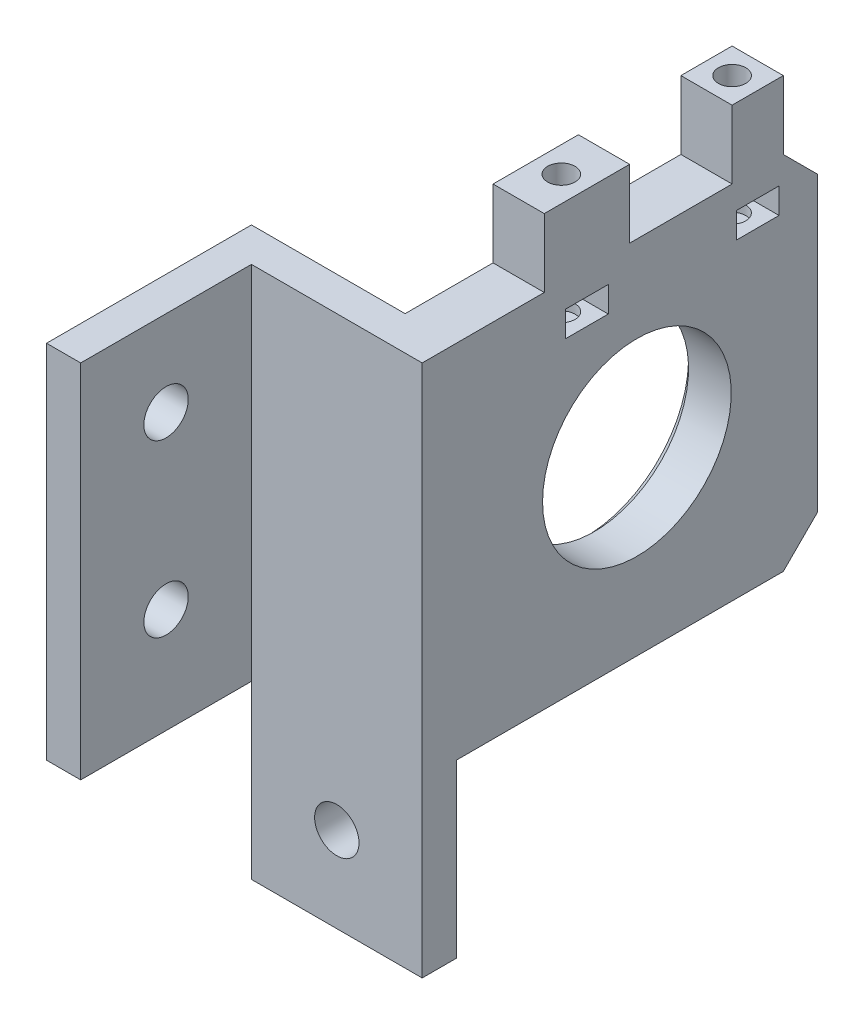
SolidWorks part; units mm, degrees
ref_plane "Přední rovina" through (0, 0, 0) normal (0, 0, 1) x (1, 0, 0)
ref_plane "Horní rovina" through (0, 0, 0) normal (0, 1, 0) x (1, 0, 0)
ref_plane "Pravá rovina" through (0, 0, 0) normal (1, 0, 0) x (0, 0, -1)
sketch "Skica2" plane through (0, 0, 0) normal (0, 0, 1) x (1, 0, 0)
  line L0 (-24.5243, -350) -> (-24.5243, 0) construction
  line L1 (-4.5243, -40) -> (-24.5243, -40)
  line L2 (-4.5243, -40) -> (-4.5243, -82.3)
  line L3 (-4.5243, -82.3) -> (-24.5243, -82.3)
  line L4 (-24.5243, -40) -> (-24.5243, -82.3)
  line L5 (-344.5243, -82.3) -> (-355.5243, -82.3) construction
extrude "Přidat vysunutím1" add sketch "Skica2" along normal blind 4
sketch "Skica3" plane through (-24.5243, 0, 0) normal (-1, 0, 0) x (0, 0, 1)
  line L0 (4, -82.3) -> (0, -82.3) construction
  line L1 (4, -40) -> (-20, -40)
  line L2 (4, -40) -> (4, -82.3)
  line L3 (4, -82.3) -> (-20, -82.3)
  line L4 (-20, -40) -> (-20, -82.3)
  line L5 (-20, -350) -> (-20, 0) construction
extrude "Přidat vysunutím2" add sketch "Skica3" along normal blind 4
sketch "Skica4" plane through (0, 0, 4) normal (0, 0, 1) x (1, 0, 0)
  line L0 (-28.5243, -82.3) -> (-4.5243, -82.3) construction
  line L1 (-10.5243, -40) -> (-4.5243, -40)
  line L2 (-10.5243, -40) -> (-10.5243, -82.3)
  line L3 (-10.5243, -82.3) -> (-4.5243, -82.3)
  line L4 (-4.5243, -40) -> (-4.5243, -82.3)
  line L5 (-4.5243, -82.3) -> (-4.5243, -40) construction
  dimension "D1" = 6
extrude "Přidat vysunutím3" add sketch "Skica4" along normal up to surface (42.3 mm away)
sketch "Skica5" plane through (-4.5243, 0, 0) normal (1, 0, 0) x (0, 0, -1)
  circle A0 centre (-25.15, -61.15) radius 11.05
  dimension "D1" = 22.1
extrude "Odebrat vysunutím1" cut sketch "Skica5" against normal blind 7
sketch "Skica7" plane through (-28.5243, 0, 0) normal (-1, 0, 0) x (0, 0, 1)
  line L0 (-20, -40) -> (-20, -82.3) construction
  line L1 (4, -40) -> (-20, -40) construction
  circle A0 centre (-10, -50) radius 2.6
  circle A1 centre (-10, -70) radius 2.6
  dimension "D3" = 5.2
  dimension "D1" = 10
  dimension "D2" = 10
  dimension "D4" = 2
extrude "Odebrat vysunutím3" cut sketch "Skica7" against normal blind 4
chamfer "Zkosení1" distance 1 angle 45 1 edges at (-10.5243, -50.1, 25.15)
sketch "Skica8" plane through (0, -82.3, 0) normal (0, -1, 0) x (1, 0, 0)
  line L0 (-28.5243, 4) -> (-10.5243, 4) construction
  line L1 (-4.5243, 0) -> (-24.5243, 0)
  line L2 (-4.5243, 0) -> (-4.5243, 4)
  line L3 (-4.5243, 4) -> (-24.5243, 4)
  line L4 (-24.5243, 0) -> (-24.5243, 4)
extrude "Přidat vysunutím4" add sketch "Skica8" along normal up to surface (20.0916 mm away)
sketch "Skica9" plane through (0, 0, 4) normal (0, 0, 1) x (1, 0, 0)
  line L0 (-24.5243, -102.3916) -> (-4.5243, -102.3916) construction
  line L1 (-4.5243, -102.3916) -> (-4.5243, -82.3) construction
  circle A0 centre (-14.5243, -92.3916) radius 2.6
  dimension "D3" = 5.2
  dimension "D1" = 10
  dimension "D2" = 10
extrude "Odebrat vysunutím4" cut sketch "Skica9" against normal blind 4
sketch "Skica10" plane through (-10.5243, 0, 0) normal (-1, 0, 0) x (0, 0, 1)
  line L0 (46.3, -44) -> (42.3, -40)
  line L1 (46.3, -40) -> (46.3, -82.3) construction
  line L2 (42.3, -40) -> (46.3, -44) construction
  line L3 (46.3, -40) -> (4, -40) construction
  line L4 (42.3, -40) -> (46.5659, -39.2593)
  line L5 (46.5659, -39.2593) -> (46.3, -44)
  line L6 (42.3, -82.3) -> (46.3, -78.3)
  line L7 (46.3, -82.3) -> (4, -82.3) construction
  line L8 (46.3, -78.3) -> (42.3, -82.3) construction
  line L9 (46.3, -78.3) -> (47.7456, -80.3)
  line L10 (47.7456, -80.3) -> (46.3, -85.4154)
  line L11 (46.3, -85.4154) -> (42.3, -82.3)
extrude "Odebrat vysunutím5" cut sketch "Skica10" against normal blind 80
mirror "Zrcadlit1" about plane through (-28.5243, -40, -20) normal (0, 0, 1) of bodies 109
sketch "Skica11" plane through (-28.5243, 0, 0) normal (-1, 0, 0) x (0, 0, 1)
  line L1 (-20, -40) -> (64.6922, -40)
  line L2 (-20, -40) -> (-20, -120.4742)
  line L3 (-20, -120.4742) -> (64.6922, -120.4742)
  line L4 (64.6922, -40) -> (64.6922, -120.4742)
extrude "Odebrat vysunutím6" cut sketch "Skica11" against normal up to surface (24 mm away) up to face at (-4.5243, -61.15, 14.1)
sketch "Skica12" plane through (0, -40, 0) normal (0, 1, 0) x (1, 0, 0)
  line L0 (-10.5243, 82.3) -> (-10.5243, 44) construction
  line L1 (-4.5243, 82.3) -> (-10.5243, 82.3)
  line L2 (-4.5243, 82.3) -> (-4.5243, 76.3)
  line L3 (-4.5243, 76.3) -> (-10.5243, 76.3)
  line L4 (-10.5243, 82.3) -> (-10.5243, 76.3)
  line L5 (-4.5243, 82.3) -> (-4.5243, 40) construction
  line L6 (-4.5243, 64.3) -> (-10.5243, 64.3)
  line L7 (-4.5243, 64.3) -> (-4.5243, 54.3)
  line L8 (-4.5243, 54.3) -> (-10.5243, 54.3)
  line L9 (-10.5243, 64.3) -> (-10.5243, 54.3)
  line L10 (-384.5243, 76.3) -> (-4.5243, 76.3) construction
  line L11 (-384.5243, 64.3) -> (-4.5243, 64.3) construction
  dimension "D1" = 10
extrude "Přidat vysunutím5" add sketch "Skica12" along normal blind 8
sketch "Skica13" plane through (0, -32, 0) normal (0, 1, 0) x (1, 0, 0)
  line L0 (-4.5243, 54.3) -> (-4.5243, 64.3) construction
  line L1 (-4.5243, 76.3) -> (-4.5243, 82.3) construction
  circle A0 centre (-7.5243, 59.3) radius 1.6
  circle A1 centre (-7.5243, 79.3) radius 1.6
  point P0 (-4.5243, 59.3)
  point P1 (-4.5243, 79.3)
  dimension "D1" = 3.2
extrude "Odebrat vysunutím7" cut sketch "Skica13" against normal blind 15
sketch "Skica14" plane through (-4.5243, 0, 0) normal (1, 0, 0) x (0, 0, -1)
  line L0 (338.2, -44.439) -> (47.5573, -44.439) construction
  line L1 (338.2, -42.939) -> (338.2, -45.939) construction
  line L2 (59.3, -32) -> (59.3, -44.439) construction
  line L3 (61.8, -42.939) -> (56.8, -42.939)
  line L4 (61.8, -42.939) -> (61.8, -45.939)
  line L5 (61.8, -45.939) -> (56.8, -45.939)
  line L6 (56.8, -42.939) -> (56.8, -45.939)
  line L7 (61.8, -42.939) -> (56.8, -45.939) construction
  line L8 (61.8, -45.939) -> (56.8, -42.939) construction
  line L9 (54.3, -32) -> (64.3, -32) construction
  line L10 (79.3, -32) -> (79.3, -44.439) construction
  line L11 (76.3, -32) -> (82.3, -32) construction
  line L13 (81.8, -45.939) -> (76.8, -45.939)
  line L14 (81.8, -45.939) -> (81.8, -42.939)
  line L15 (81.8, -42.939) -> (76.8, -42.939)
  line L16 (76.8, -45.939) -> (76.8, -42.939)
  line L17 (81.8, -45.939) -> (76.8, -42.939) construction
  line L18 (81.8, -42.939) -> (76.8, -45.939) construction
  point P4 (59.3, -44.439)
  dimension "D1" = 5
  dimension "D2" = 3
extrude "Odebrat vysunutím8" cut sketch "Skica14" against normal blind 15
